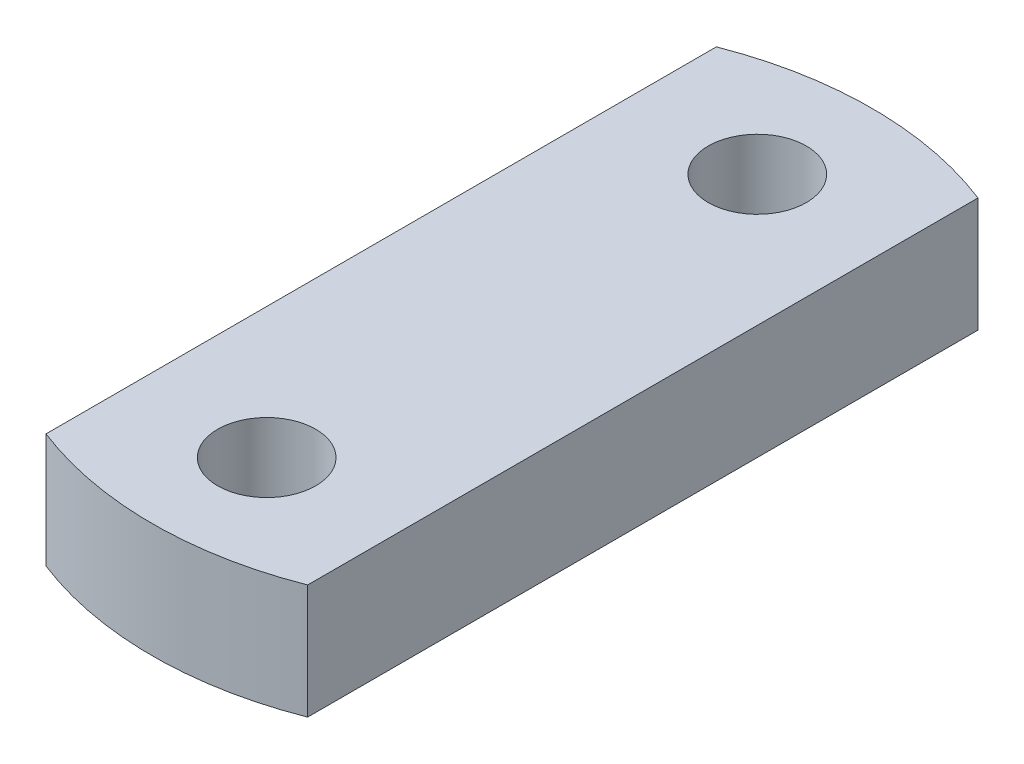
SolidWorks part; units mm, degrees
ref_plane "Front Plane" through (0, 0, 0) normal (0, 0, 1) x (1, 0, 0)
ref_plane "Top Plane" through (0, 0, 0) normal (0, 1, 0) x (1, 0, 0)
ref_plane "Right Plane" through (0, 0, 0) normal (1, 0, 0) x (0, 0, -1)
sketch "Sketch1" plane through (0, 0, 0) normal (0, 1, 0) x (1, 0, 0)
  line L0 (-98.4, 0) -> (113.2, 0) construction
  line L1 (0, 75) -> (0, -75) construction
  line L2 (-40, 102.4695) -> (-40, -102.4695)
  line L3 (40, 102.4695) -> (40, -102.4695)
  arc A3 (-40, -102.4695) -> (40, -102.4695) centre (0, 0) ccw
  arc A4 (40, 102.4695) -> (-40, 102.4695) centre (0, 0) ccw
  circle A5 centre (0, 75) radius 15
  circle A6 centre (0, -75) radius 15
  dimension "D3" = 150
  dimension "D4" = 75
  dimension "D5" = 220
  dimension "D6" = 75
  dimension "D7" = 30
  dimension "D8" = 30
  dimension "D1" = 40
  dimension "D2" = 40
extrude "Boss-Extrude1" add sketch "Sketch1" along normal blind 35
